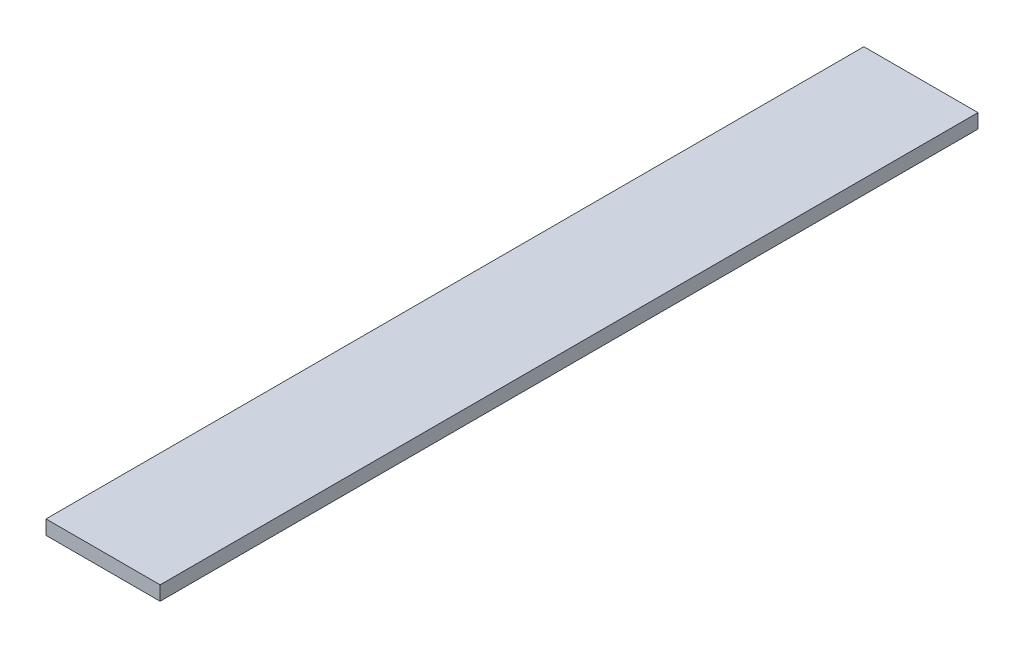
SolidWorks part; units mm, degrees
ref_plane "Front Plane" through (0, 0, 0) normal (0, 0, 1) x (1, 0, 0)
ref_plane "Top Plane" through (0, 0, 0) normal (0, 1, 0) x (1, 0, 0)
ref_plane "Right Plane" through (0, 0, 0) normal (1, 0, 0) x (0, 0, -1)
sketch "Sketch1" plane through (0, 0, 0) normal (0, 1, 0) x (1, 0, 0)
  line L1 (76.2, 546.1) -> (-76.2, 546.1)
  line L2 (76.2, 546.1) -> (76.2, -546.1)
  line L3 (76.2, -546.1) -> (-76.2, -546.1)
  line L4 (-76.2, 546.1) -> (-76.2, -546.1)
  line L5 (76.2, 546.1) -> (-76.2, -546.1) construction
  line L6 (76.2, -546.1) -> (-76.2, 546.1) construction
  point P0 (0, 0)
  dimension "D1" = 152.4
  dimension "D2" = 1092.2
extrude "Boss-Extrude1" add sketch "Sketch1" along normal mid plane 19.05
